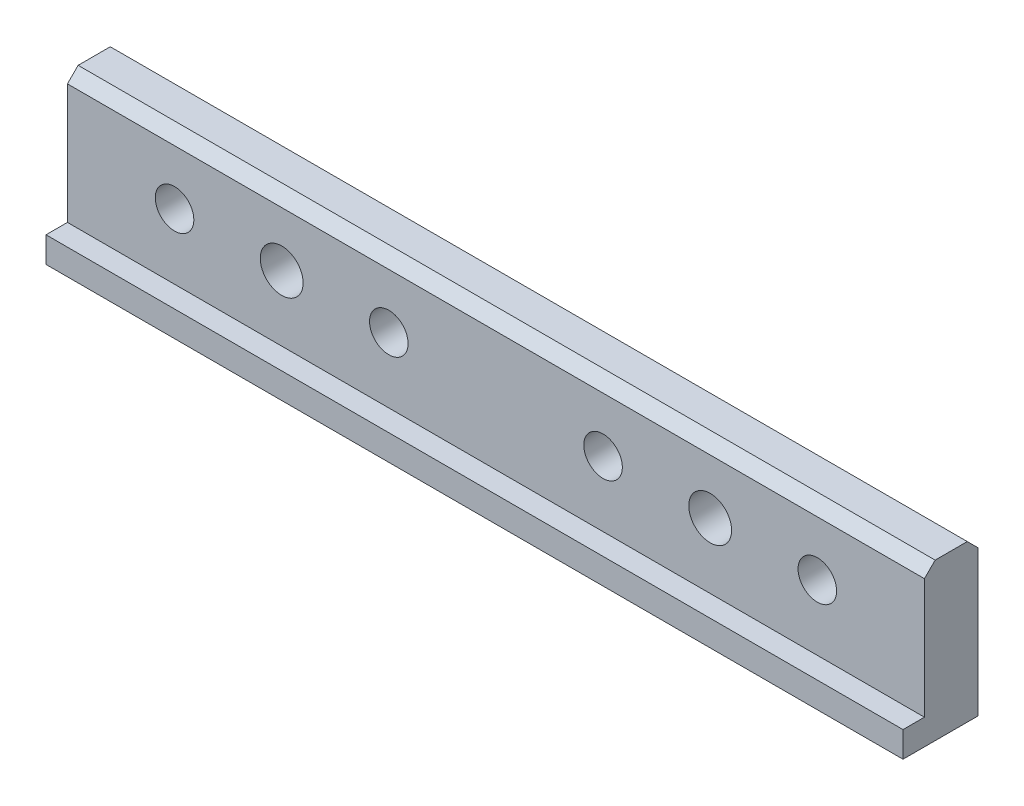
SolidWorks part; units mm, degrees
ref_plane "前视基准面" through (0, 0, 0) normal (0, 0, 1) x (1, 0, 0)
ref_plane "上视基准面" through (0, 0, 0) normal (0, 1, 0) x (1, 0, 0)
ref_plane "右视基准面" through (0, 0, 0) normal (1, 0, 0) x (0, 0, -1)
sketch "草图1" plane through (0, 0, 0) normal (0, 0, 1) x (1, 0, 0)
  line L1 (-200, 40) -> (200, 40)
  line L2 (-200, 40) -> (-200, -40)
  line L3 (-200, -40) -> (200, -40)
  line L4 (200, 40) -> (200, -40)
  line L5 (-200, 40) -> (200, -40) construction
  line L6 (-200, -40) -> (200, 40) construction
  point P0 (0, 0)
  dimension "D1" = 400
  dimension "D2" = 80
extrude "凸台-拉伸1" add sketch "草图1" along normal blind 35
sketch "草图2" plane through (0, 0, 35) normal (0, 0, 1) x (1, 0, 0)
  line L0 (200, -40) -> (200, 40) construction
  line L1 (-200, 40) -> (200, 40)
  line L2 (-200, 40) -> (-200, -21)
  line L3 (-200, -21) -> (200, -21)
  line L4 (200, 40) -> (200, -21)
  line L5 (-200, -40) -> (200, -40) construction
  dimension "D1" = 19
extrude "切除-拉伸1" cut sketch "草图2" against normal blind 10
chamfer "倒角1" distance 5 angle 45 2 edges at (0, 40, 0) (0, 40, 25)
chamfer "倒角2" distance 10 angle 35 1 edges at (0, -40, 35)
chamfer "倒角3" distance 10 angle 35 1 edges at (0, -40, 0)
chamfer "倒角4" distance 10 angle 35 1 edges at (-200, -40, 17.5)
chamfer "倒角5" distance 10 angle 35 1 edges at (200, -40, 17.5)
sketch "草图3" plane through (0, 0, 25) normal (0, 0, 1) x (1, 0, 0)
  line L0 (-200, 35) -> (-200, -21) construction
  line L1 (-200, -21) -> (200, -21) construction
  circle A0 centre (-150, 9.5) radius 9
  circle A1 centre (-100, 9.5) radius 10
  circle A2 centre (-50, 9.5) radius 9
  circle A3 centre (50, 9.5) radius 9
  circle A4 centre (100, 9.5) radius 10
  circle A5 centre (150, 9.5) radius 9
  point P12 (0, 0)
  dimension "D1" = 100
  dimension "D2" = 100
  dimension "D3" = 100
  dimension "D4" = 200
  dimension "D5" = 50
  dimension "D6" = 100
  dimension "D7" = 18
  dimension "D8" = 20
  dimension "D9" = 18
  dimension "D10" = 18
  dimension "D11" = 20
  dimension "D12" = 18
  dimension "D13" = 30.5
extrude "切除-拉伸2" cut sketch "草图3" against normal up to next
